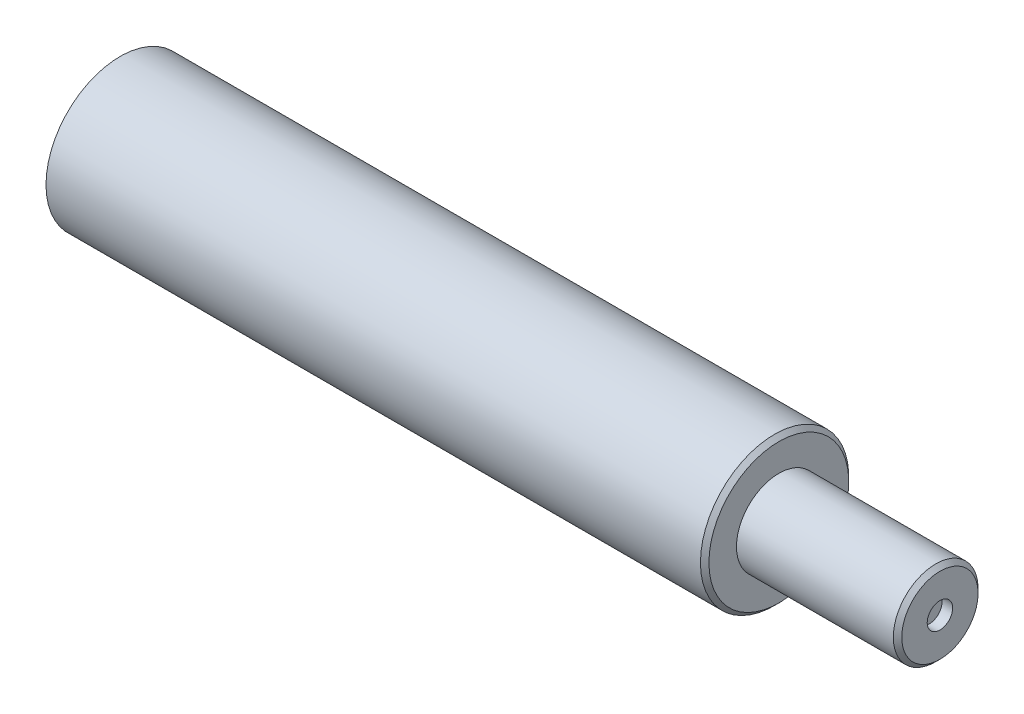
SolidWorks part; units mm, degrees
material "1023 Carbon Steel Sheet (SS)"
ref_plane "Front Plane" through (0, 0, 0) normal (0, 0, 1) x (1, 0, 0)
ref_plane "Top Plane" through (0, 0, 0) normal (0, 1, 0) x (1, 0, 0)
ref_plane "Right Plane" through (0, 0, 0) normal (1, 0, 0) x (0, 0, -1)
sketch "Sketch1" plane through (0, 0, 0) normal (0, 0, 1) x (1, 0, 0)
  line L0 (0, 0) -> (190.9, 0) construction
  line L1 (55, 0) -> (-55, 0) construction
  line L3 (190.9, 0) -> (190.9, 3)
  line L6 (0, 17.5) -> (155.4, 17.5)
  line L7 (155.4, 17.5) -> (155.4, 10)
  line L8 (190.9, 0) -> (0, 0)
  line L9 (155.4, 10) -> (193.4, 10)
  line L10 (193.4, 10) -> (193.4, 3)
  line L13 (190.9, 3) -> (193.4, 3)
  line L18 (0, 17.5) -> (0, 0)
  line L19 (198.4, 0) -> (221.0251, 0) construction
  point P6 (0, 0)
  dimension "D1" = 35
  dimension "D4" = 155.4
  dimension "D5" = 20
  dimension "D6" = 38
  dimension "D7" = 6
  dimension "D8" = 2.5
revolve "Revolve1" add sketch "Sketch1" angle 360 about L0
chamfer "Chamfer1" distance 1 angle 45 2 edges at (155.4, 0, 17.5) (193.4, 0, 10)
sketch "Sketch2" plane through (0, 0, 0) normal (-1, 0, 0) x (0, 0, 1)
  line L0 (0, -18.7) -> (0, 18.7) construction
  line L1 (55, 0) -> (-55, 0) construction
  circle A0 centre (-7, 7) radius 2.5
  circle A1 centre (7, 7) radius 2.5
  circle A2 centre (7, -7) radius 2.5
  circle A3 centre (-7, -7) radius 2.5
  dimension "D3" = 5
  dimension "D1" = 14
  dimension "D2" = 14
extrude "Cut-Extrude1" cut sketch "Sketch2" against normal blind 27
cosmetic thread "Cosmetic Thread1" parameters "D1"=25, "D2"=6
cosmetic thread "Cosmetic Thread2" parameters "D1"=25, "D2"=6
cosmetic thread "Cosmetic Thread3" parameters "D1"=25, "D2"=6
cosmetic thread "Cosmetic Thread4" parameters "D1"=25, "D2"=6
